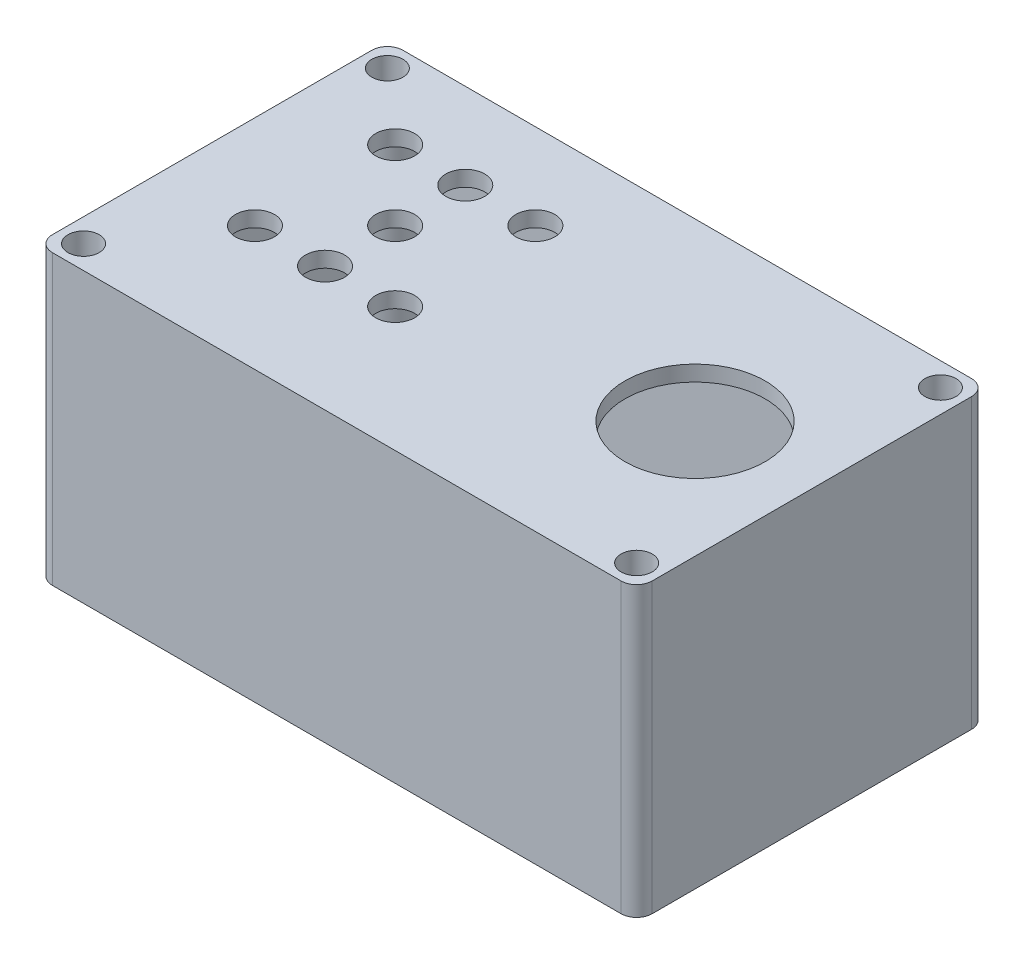
SolidWorks part; units mm, degrees
ref_plane "Front Plane" through (0, 0, 0) normal (0, 0, 1) x (1, 0, 0)
ref_plane "Top Plane" through (0, 0, 0) normal (0, 1, 0) x (1, 0, 0)
ref_plane "Right Plane" through (0, 0, 0) normal (1, 0, 0) x (0, 0, -1)
sketch "Sketch2" plane through (0, 0, 0) normal (0, 1, 0) x (1, 0, 0)
  line L1 (-38.5, -22.5) -> (38.5, -22.5)
  line L2 (-38.5, -22.5) -> (-38.5, 22.5)
  line L3 (-38.5, 22.5) -> (38.5, 22.5)
  line L4 (38.5, -22.5) -> (38.5, 22.5)
  line L5 (-38.5, -22.5) -> (38.5, 22.5) construction
  line L6 (-38.5, 22.5) -> (38.5, -22.5) construction
  point P0 (0, 0)
  dimension "D1" = 77
  dimension "D2" = 45
extrude "Boss-Extrude1" add sketch "Sketch2" along normal blind 37
sketch "Sketch24" plane through (0, 0, 0) normal (0, -1, 0) x (1, 0, 0)
  line L0 (0, 0) -> (0, 9.234) construction
  line L1 (0, 0) -> (7.1308, 0) construction
  line L2 (-38.5, -22.5) -> (-38.5, 22.5) construction
  line L3 (-38.5, 22.5) -> (38.5, 22.5) construction
  circle A0 centre (-35.5, 19.5) radius 2
  circle A1 centre (35.5, 19.5) radius 2
  circle A2 centre (35.5, -19.5) radius 2
  circle A3 centre (-35.5, -19.5) radius 2
  dimension "D1" = 4
  dimension "D2" = 3
  dimension "D3" = 3
extrude "Cut-Extrude13" cut sketch "Sketch24" against normal through all
shell "Shell2" thickness 2
sketch "Sketch5" plane through (0, 37, 0) normal (0, 1, 0) x (1, 0, 0)
  line L0 (38.5, 22.5) -> (-38.5, 22.5) construction
  line L4 (-31.5, 19.5) -> (-31.5, -19.5) construction
  circle A0 centre (-26.5, 11.5) radius 2.5
  arc A1 (-36.5, 15.627) -> (-31.627, 20.5) centre (-35.5, 19.5) ccw construction
  arc A2 (-36.5, 15.627) -> (-31.627, 20.5) centre (-35.5, 19.5) ccw construction
  arc A3 (-31.627, -20.5) -> (-36.5, -15.627) centre (-35.5, -19.5) ccw construction
  arc A4 (-31.627, -20.5) -> (-36.5, -15.627) centre (-35.5, -19.5) ccw construction
  dimension "D1" = 5
  dimension "D2" = 11
  dimension "D4" = 5
extrude "Cut-Extrude1" cut sketch "Sketch5" against normal through all
pattern_linear "LPattern1" count 3 spacing 9 along (1, 0, 0) of "Cut-Extrude1"
pattern_linear "LPattern2" count 3 spacing 9 along (0, 0, 1) count 3 spacing 9 along (1, 0, 0) skipping (1, 0), (1, 2) of "Cut-Extrude1"
sketch "Sketch19" plane through (0, 37, 0) normal (0, 1, 0) x (1, 0, 0)
  line L0 (38.5, -22.5) -> (38.5, 22.5) construction
  line L2 (31.5, 19.5) -> (31.5, -19.5) construction
  circle A0 centre (23.5, 0) radius 9
  arc A1 (31.627, 20.5) -> (36.5, 15.627) centre (35.5, 19.5) ccw construction
  arc A2 (31.627, 20.5) -> (36.5, 15.627) centre (35.5, 19.5) ccw construction
  arc A3 (36.5, -15.627) -> (31.627, -20.5) centre (35.5, -19.5) ccw construction
  point P4 (38.5, 0)
  dimension "D1" = 18
  dimension "D3" = 0
  dimension "D2" = 8
extrude "Cut-Extrude11" cut sketch "Sketch19" against normal blind 2
fillet "Fillet1" radius 2 4 edges at (38.5, 18.5, -22.5) (38.5, 18.5, 22.5) (-38.5, 18.5, 22.5) (-38.5, 18.5, -22.5)
